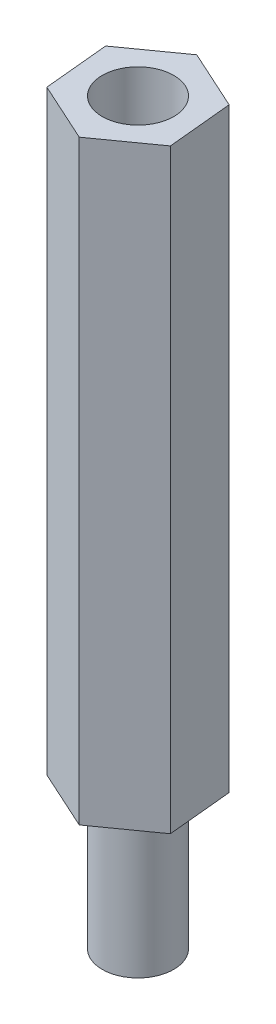
SolidWorks part; units mm, degrees
ref_plane "前视基准面" through (0, 0, 0) normal (0, 0, 1) x (1, 0, 0)
ref_plane "上视基准面" through (0, 0, 0) normal (0, 1, 0) x (1, 0, 0)
ref_plane "右视基准面" through (0, 0, 0) normal (1, 0, 0) x (0, 0, -1)
sketch "草图1" plane through (0, 0, 0) normal (0, 1, 0) x (1, 0, 0)
  circle A0 centre (0, 0) radius 1.5
  dimension "D1" = 3
extrude "凸台-拉伸1" add sketch "草图1" along normal blind 6
sketch "草图2" plane through (0, 6, 0) normal (0, 1, 0) x (1, 0, 0)
  line L1 (2.4958, -1.1366) -> (2.2322, 1.5931)
  line L2 (2.2322, 1.5931) -> (-0.2636, 2.7297)
  line L3 (-0.2636, 2.7297) -> (-2.4958, 1.1366)
  line L4 (-2.4958, 1.1366) -> (-2.2322, -1.5931)
  line L5 (-2.2322, -1.5931) -> (0.2636, -2.7297)
  line L6 (0.2636, -2.7297) -> (2.4958, -1.1366)
  circle A0 centre (0, 0) radius 2.375 construction
  dimension "D1" = 4.75
extrude "凸台-拉伸2" add sketch "草图2" along normal blind 25
sketch "草图3" plane through (0, 31, 0) normal (0, 1, 0) x (1, 0, 0)
  circle A0 centre (0, 0) radius 1.5
  dimension "D1" = 3
extrude "切除-拉伸1" cut sketch "草图3" against normal blind 5
